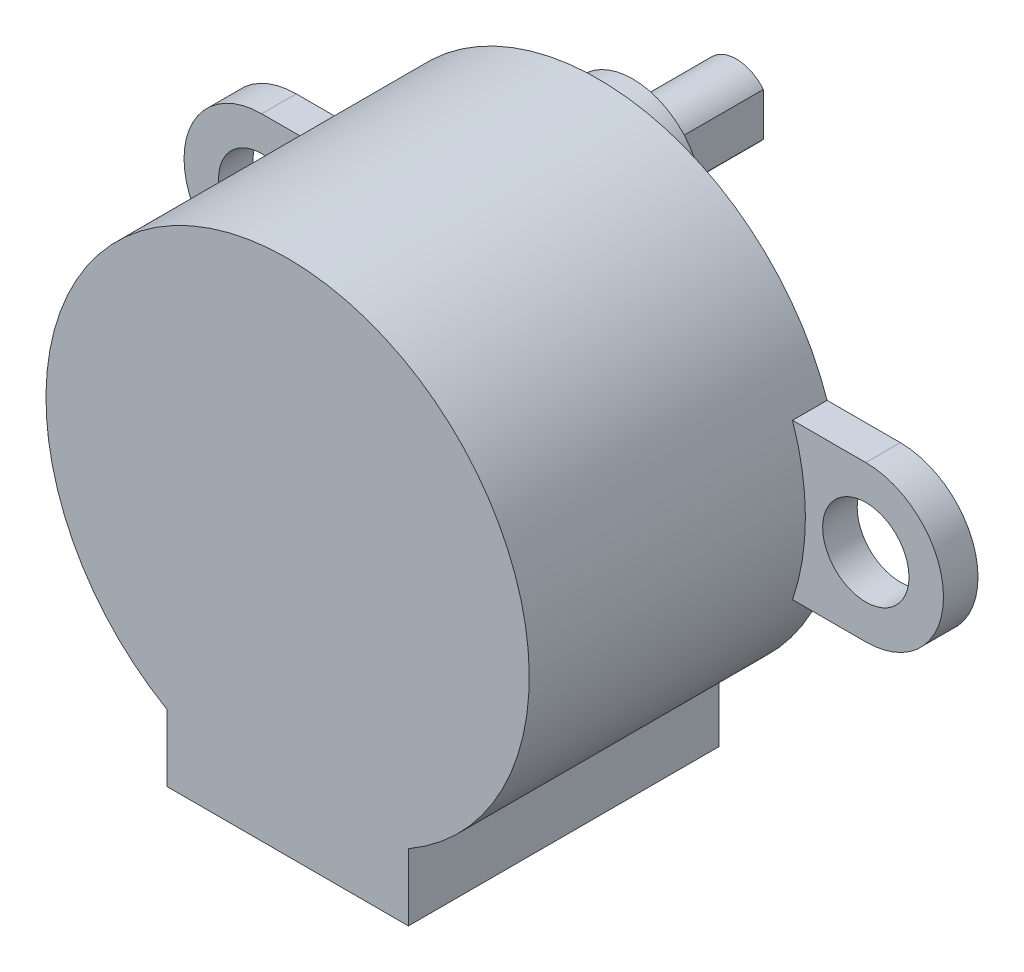
SolidWorks part; units mm, degrees
ref_plane "Alzado" through (0, 0, 0) normal (0, 0, 1) x (1, 0, 0)
ref_plane "Planta" through (0, 0, 0) normal (0, 1, 0) x (1, 0, 0)
ref_plane "Vista lateral" through (0, 0, 0) normal (1, 0, 0) x (0, 0, -1)
sketch "Croquis1" plane through (0, 0, 0) normal (0, 0, 1) x (1, 0, 0)
  line L0 (0, -14) -> (0, -16)
  line L1 (0, -16) -> (7, -16)
  line L2 (0, -16) -> (-7, -16)
  line L3 (-7, -16) -> (-7, -12.1244)
  line L4 (7, -16) -> (7, -12.1244)
  line L5 (-7, -16) -> (0, -16)
  circle A0 centre (0, 0) radius 14
  dimension "D1" = 28
  dimension "D2" = 2
  dimension "D3" = 7
  dimension "D4" = 7
extrude "Saliente-Extruir1" add sketch "Croquis1" along normal blind 18 contours A0 | A0 L0 L1 L4 | A0 L3 L2 L0
sketch "Croquis2" plane through (0, 0, 0) normal (0, 0, -1) x (-1, 0, 0)
  line L0 (0, 0) -> (-14, 0)
  line L1 (-14, 0) -> (-20, 0)
  line L2 (0, 0) -> (0, 3.1619)
  line L3 (-20, 0) -> (-17.5, 0)
  line L4 (-17.5, 4.5) -> (-13.2571, 4.5)
  line L5 (-17.5, -4.5) -> (-13.2571, -4.5)
  line L6 (17.5, -4.5) -> (13.2571, -4.5)
  line L7 (17.5, 4.5) -> (13.2571, 4.5)
  line L8 (20, 0) -> (17.5, 0)
  line L9 (14, 0) -> (20, 0)
  arc A0 (7, -12.1244) -> (-7, -12.1244) centre (0, 0) ccw construction
  circle A1 centre (-17.5, 0) radius 2.5
  arc A2 (-17.5, 4.5) -> (-17.5, -4.5) centre (-17.5, 0) ccw
  arc A4 (17.5, 4.5) -> (17.5, -4.5) centre (17.5, 0) cw
  circle A5 centre (17.5, 0) radius 2.5
  arc A6 (-13.2571, -4.5) -> (-13.2571, 4.5) centre (0, 0) cw
  arc A7 (13.2571, 4.5) -> (13.2571, -4.5) centre (0, 0) cw
  dimension "D3" = 2.5
extrude "Saliente-Extruir3" add sketch "Croquis2" against normal blind 2
sketch "Croquis3" plane through (0, 0, 0) normal (0, 0, -1) x (-1, 0, 0)
  line L0 (0, 14) -> (0, 13)
  line L1 (0, 13) -> (0, 5)
  arc A1 (13.2571, 4.5) -> (-13.2571, 4.5) centre (0, 0) ccw construction
  circle A2 centre (0, 9) radius 4
  dimension "D1" = 1
  dimension "D2" = 8
extrude "Saliente-Extruir4" add sketch "Croquis3" along normal blind 2 contours L1 A2 | L1 A2
sketch "Croquis4" plane through (0, 0, -2) normal (0, 0, -1) x (-1, 0, 0)
  line L0 (-1.5612, 10.25) -> (-1.5612, 7.75)
  line L1 (0, 9) -> (0, 9.6089)
  line L2 (1.5612, 10.25) -> (1.5612, 7.75)
  circle A0 centre (0, 9) radius 2
  dimension "D1" = 4
  dimension "D2" = 2.5
extrude "Saliente-Extruir5" add sketch "Croquis4" along normal blind 6
